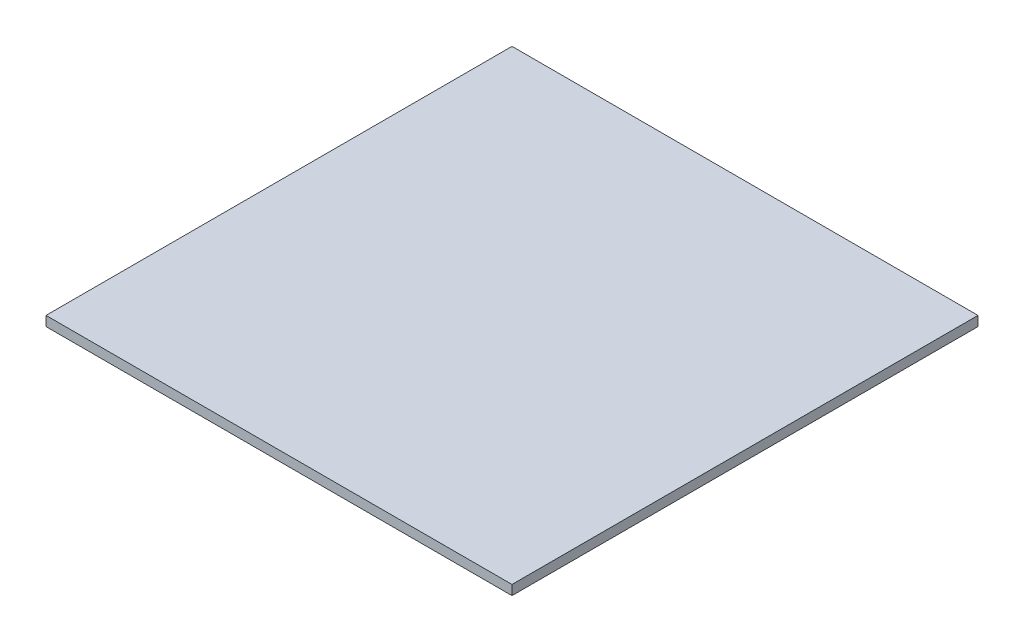
SolidWorks part; units mm, degrees
ref_plane "Front Plane" through (0, 0, 0) normal (0, 0, 1) x (1, 0, 0)
ref_plane "Top Plane" through (0, 0, 0) normal (0, 1, 0) x (1, 0, 0)
ref_plane "Right Plane" through (0, 0, 0) normal (1, 0, 0) x (0, 0, -1)
sketch "Sketch1" plane through (0, 0, 0) normal (0, 1, 0) x (1, 0, 0)
  line L4 (-48, -48) -> (-48, 48)
  line L5 (-48, 48) -> (48, 48)
  line L6 (48, -48) -> (-48, -48)
  line L7 (48, 48) -> (48, -48)
extrude "Boss-Extrude1" add sketch "Sketch1" along normal blind 2
